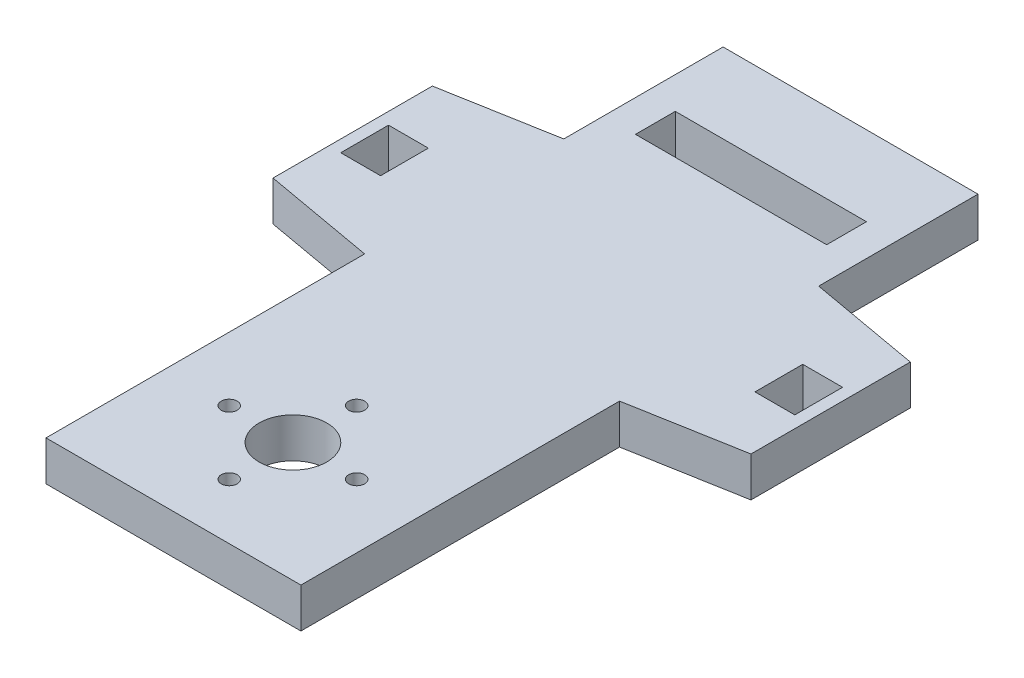
SolidWorks part; units mm, degrees
ref_plane "Front Plane" through (0, 0, 0) normal (0, 0, 1) x (1, 0, 0)
ref_plane "Top Plane" through (0, 0, 0) normal (0, 1, 0) x (1, 0, 0)
ref_plane "Right Plane" through (0, 0, 0) normal (1, 0, 0) x (0, 0, -1)
sketch "Sketch1" plane through (0, 0, 0) normal (0, 1, 0) x (1, 0, 0)
  line L0 (-16, -42.5) -> (16, -42.5)
  line L1 (16, -42.5) -> (16, -2.5)
  line L2 (16, -2.5) -> (30, 0)
  line L3 (30, 0) -> (30, 20)
  line L4 (30, 20) -> (16, 22.5)
  line L5 (16, 22.5) -> (16, 42.5)
  line L6 (16, 42.5) -> (-16, 42.5)
  line L7 (-16, 42.5) -> (-16, 22.5)
  line L8 (-16, 22.5) -> (-30, 20)
  line L9 (-30, 20) -> (-30, 0)
  line L10 (-30, 0) -> (-16, -2.5)
  line L11 (-16, -2.5) -> (-16, -42.5)
  point P9 (30, 10)
  dimension "D1" = 40
  dimension "D2" = 40
  dimension "D3" = 32
  dimension "D4" = 32
  dimension "D5" = 60
  dimension "D6" = 20
  dimension "D7" = 20
  dimension "D8" = 14
  dimension "D9" = 14
  dimension "D10" = 16
  dimension "D11" = 85
  dimension "D12" = 42.5
  dimension "D13" = 20
  dimension "D14" = 20
  dimension "D15" = 2.5
  dimension "D16" = 2.5
extrude "Boss-Extrude1" add sketch "Sketch1" along normal blind 5
sketch "Sketch2" plane through (0, 5, 0) normal (0, 1, 0) x (1, 0, 0)
  line L5 (-16, 42.5) -> (-16, 22.5) construction
  line L6 (-28.5, 13) -> (-28.5, 7)
  line L7 (-28.5, 7) -> (-23.5, 7)
  line L8 (-23.5, 7) -> (-23.5, 13)
  line L11 (-28.5, 13) -> (-23.5, 13)
  line L12 (-30, 20) -> (-30, 0) construction
  line L13 (23.5, 13) -> (28.5, 13)
  line L14 (28.5, 13) -> (28.5, 7)
  line L15 (28.5, 7) -> (23.5, 7)
  line L16 (23.5, 7) -> (23.5, 13)
  line L17 (30, 0) -> (30, 20) construction
  line L20 (-12, 32.5) -> (12, 32.5)
  line L21 (-12, 32.5) -> (-12, 27.5)
  line L22 (-12, 27.5) -> (12, 27.5)
  line L23 (12, 32.5) -> (12, 27.5)
  line L24 (16, 42.5) -> (-16, 42.5) construction
  line L25 (-16, -2.5) -> (-16, -42.5) construction
  line L26 (-16, -42.5) -> (16, -42.5) construction
  circle A4 centre (0, -27.5) radius 4.25
  circle A5 centre (-8, -27.5) radius 1
  circle A6 centre (0, -19.5) radius 1
  circle A7 centre (8, -27.5) radius 1
  circle A8 centre (0, -35.5) radius 1
  dimension "D5" = 2
  dimension "D6" = 2
  dimension "D7" = 2
  dimension "D8" = 2
  dimension "D27" = 8.5
  dimension "D3" = 16
  dimension "D4" = 15
  dimension "D9" = 8
  dimension "D10" = 8
  dimension "D11" = 8
  dimension "D12" = 8
  dimension "D13" = 16
  dimension "D14" = 16
  dimension "D15" = 24
  dimension "D16" = 5
  dimension "D17" = 1.5
  dimension "D18" = 6
  dimension "D19" = 5
  dimension "D20" = 7
  dimension "D21" = 5
  dimension "D22" = 6
  dimension "D23" = 1.5
  dimension "D24" = 7
  dimension "D25" = 4
  dimension "D26" = 10
  dimension "D28" = 15
  dimension "D29" = 15
extrude "Cut-Extrude1" cut sketch "Sketch2" against normal blind 5
